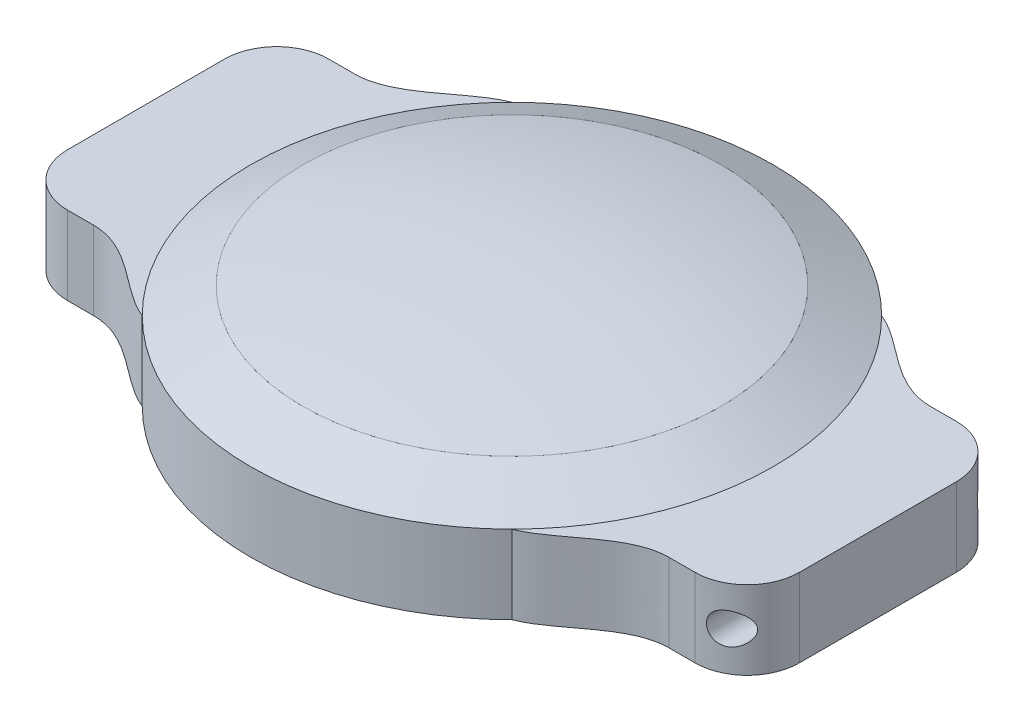
SolidWorks part; units mm, degrees
ref_plane "Front Plane" through (0, 0, 0) normal (0, 0, 1) x (1, 0, 0)
ref_plane "Top Plane" through (0, 0, 0) normal (0, 1, 0) x (1, 0, 0)
ref_plane "Right Plane" through (0, 0, 0) normal (1, 0, 0) x (0, 0, -1)
sketch "Sketch1" plane through (0, 0, 0) normal (0, 0, 1) x (1, 0, 0)
  line L0 (0, 0) -> (0.5, 0)
  line L1 (0.5, 0) -> (0.5, 0.15)
  line L2 (0.5, 0.15) -> (0.4, 0.2)
  line L3 (0.4, 0.2) -> (0, 0.2)
  line L4 (0, 0.2) -> (0, 0)
  dimension "D1" = 0.5
  dimension "D2" = 0.2
  dimension "D3" = 0.15
  dimension "D4" = 0.4
revolve "Revolve1" add sketch "Sketch1" angle 360 about L4
sketch "Sketch2" plane through (0, 0.2, 0) normal (0, 1, 0) x (1, 0, 0)
  circle A0 centre (0, 0) radius 0.35
  circle A1 centre (0, 0) radius 0.4 construction
  dimension "D1" = 0.05
extrude "Cut-Extrude2" cut sketch "Sketch2" against normal blind 0.05
sketch "Sketch3" plane through (0, 0.15, 0) normal (0, 1, 0) x (1, 0, 0)
  line L0 (0, 0) -> (0, 0.27) construction
  line L1 (-0.01, 0.35) -> (0.01, 0.35)
  line L2 (-0.01, 0.35) -> (-0.01, 0.19)
  line L3 (-0.01, 0.19) -> (0.01, 0.19)
  line L4 (0.01, 0.35) -> (0.01, 0.19)
  line L5 (-0.01, 0.35) -> (0.01, 0.19) construction
  line L6 (-0.01, 0.19) -> (0.01, 0.35) construction
  circle A0 centre (0, 0) radius 0.35 construction
  point P0 (0, 0.27)
  dimension "D1" = 0.27
  dimension "D2" = 0.02
extrude "Cut-Extrude3" cut sketch "Sketch3" against normal blind 0.01
pattern_circular "CirPattern1" count 12 over 360 about axis through (0, 0, 0.0023) along (0, 1, 0) of "Cut-Extrude3"
sketch "Sketch4" plane through (0, 0, 0) normal (0, 0, 1) x (1, 0, 0)
  line L0 (0, 0) -> (0, 0.15) construction
  line L1 (-0.5, 0) -> (0.5, 0) construction
  line L2 (-0.5, 0.15) -> (0.5, 0.15) construction
  line L3 (0, 0.15) -> (0.15, 0.15)
  line L4 (0, 0.17) -> (0, 0.15)
  arc A0 (0.15, 0.15) -> (0, 0.17) centre (0.0003, -0.4) ccw
  dimension "D2" = 0.02
  dimension "D3" = 0.57
  dimension "D1" = 0.15
revolve "Revolve2" add sketch "Sketch4" angle 360 about L0
sketch "Sketch6" plane through (0, 0.15, 0) normal (0, 1, 0) x (1, 0, 0)
  circle A0 centre (0, 0) radius 0.025
  dimension "D1" = 0.05
extrude "Boss-Extrude2" add sketch "Sketch6" along normal blind 0.02
sketch "Sketch7" plane through (0, 0.17, 0) normal (0, 1, 0) x (1, 0, 0)
  line L0 (0, 0) -> (0.1515, 0.2589) construction
  line L1 (-0.0129, 0.0076) -> (0.1386, 0.2665)
  line L2 (0.0129, -0.0076) -> (0.1645, 0.2513)
  line L3 (0.0875, 0.1692) -> (0.1048, 0.1592) construction
  arc A0 (-0.0129, 0.0076) -> (0.0129, -0.0076) centre (0, 0) ccw
  arc A1 (0.1645, 0.2513) -> (0.1386, 0.2665) centre (0.1515, 0.2589) ccw
  point P3 (0.0758, 0.1295)
  point P10 (0.0961, 0.1642)
  dimension "D1" = 0.3
  dimension "D2" = 0.03
extrude "Boss-Extrude3" add sketch "Sketch7" along normal blind 0.01
sketch "Sketch9" plane through (0, 0.17, 0) normal (0, 1, 0) x (1, 0, 0)
  line L0 (0, 0) -> (-0.127, 0.1545) construction
  line L1 (-0.0116, -0.0095) -> (-0.1386, 0.145)
  line L2 (0.0116, 0.0095) -> (-0.1154, 0.164)
  line L3 (-0.127, 0.1545) -> (-0.2222, 0.2704) construction
  arc A0 (-0.0116, -0.0095) -> (0.0116, 0.0095) centre (0, 0) ccw
  arc A1 (-0.1154, 0.164) -> (-0.1386, 0.145) centre (-0.127, 0.1545) ccw
  arc A2 (-0.1846, 0.2974) -> (-0.299, 0.1819) centre (0, 0) ccw construction
  point P3 (-0.0635, 0.0773)
  dimension "D1" = 0.2
  dimension "D2" = 0.03
extrude "Boss-Extrude4" add sketch "Sketch9" along normal blind 0.01
sketch "Sketch8" plane through (0, 0, 0) normal (0, 0, 1) x (1, 0, 0)
  line L0 (0, 0) -> (0, 0.2) construction
  line L1 (0.4, 0.2) -> (-0.4, 0.2) construction
  line L2 (0, 0.2) -> (0, 0.23) construction
  line L3 (0, 0.23) -> (0, 0.25)
  line L4 (0, 0.25) -> (0.0514, 0.25) construction
  line L5 (0.35, 0.2) -> (-0.35, 0.2) construction
  line L6 (-0.4, 0.2) -> (-0.35, 0.2)
  arc A0 (0, 0.25) -> (-0.4, 0.2) centre (0.0006, -1.38) ccw
  arc A1 (0, 0.23) -> (-0.35, 0.2) centre (0.0491, -2.3995) ccw
  dimension "D1" = 1.63
  dimension "D2" = 2.63
  dimension "D3" = 0.02
  dimension "D4" = 0.03
  dimension "D5" = 0.05
revolve "Revolve3" add sketch "Sketch8" angle 360 about L3
sketch "Sketch10" plane through (0, 0, 0) normal (0, -1, 0) x (1, 0, 0)
  line L0 (0.55, -0.25) -> (0.7, -0.25)
  line L1 (0, 0) -> (0.3536, 0.3536) construction
  line L2 (0, 0) -> (0.3536, -0.3536) construction
  line L3 (0.3536, 0.3536) -> (0.3536, -0.3536)
  line L4 (0.5, 0) -> (0.65, 0) construction
  line L5 (0.65, 0) -> (0.7, 0) construction
  line L6 (0.7, -0.25) -> (0.7, 0.25)
  line L9 (0.55, 0.25) -> (0.7, 0.25)
  circle A0 centre (0, 0) radius 0.5 construction
  spline S0 degree 3 poles (0.55, -0.25) (0.474, -0.25) (0.4134, -0.3309) (0.3536, -0.3536) knots 0 0 0 0 1 1 1 1
  spline S1 degree 3 poles (0.55, 0.25) (0.474, 0.25) (0.4134, 0.3309) (0.3536, 0.3536) knots 0 0 0 0 1 1 1 1
  point P11 (0.7, 0)
  dimension "D1" = 90
  dimension "D3" = 0.15
  dimension "D4" = 0.05
  dimension "D5" = 0.5
  dimension "D6" = 0.15
extrude "Boss-Extrude5" add sketch "Sketch10" against normal up to surface (0.15 mm away) up to face at (-0.15, 0.15, 0)
fillet "Fillet2" radius 0.1 2 edges at (0.7, 0.075, -0.25) (0.7, 0.075, 0.25)
mirror "Mirror1" about plane through (0, 0, 0) normal (1, 0, 0) of "Fillet2", "Boss-Extrude5"
sketch "Sketch11" plane through (0, 0, 0.25) normal (0, 0, 1) x (1, 0, 0)
  line L0 (0.7, 0.15) -> (0.6, 0.15) construction
  line L1 (0.65, 0.15) -> (0.65, 0) construction
  line L2 (0.6, 0) -> (0.7, 0) construction
  circle A0 centre (0.65, 0.075) radius 0.03
  point P8 (0.65, 0.075)
  dimension "D1" = 0.06
extrude "Cut-Extrude4" cut sketch "Sketch11" against normal through all and the other way through all
